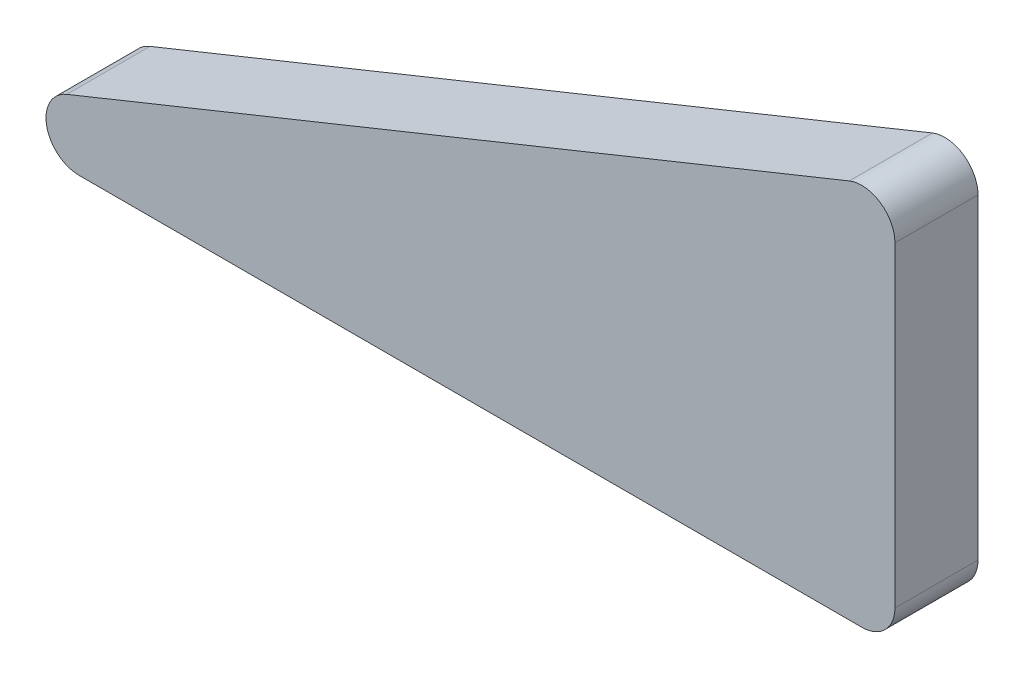
SolidWorks part; units mm, degrees
ref_plane "Front" through (0, 0, 0) normal (0, 0, 1) x (1, 0, 0)
ref_plane "Top" through (0, 0, 0) normal (0, 1, 0) x (1, 0, 0)
ref_plane "Right" through (0, 0, 0) normal (1, 0, 0) x (0, 0, -1)
sketch "Sketch1" plane through (0, 0, 0) normal (0, 0, 1) x (1, 0, 0)
  line L0 (0, 0) -> (29.6917, 0) construction
  line L1 (29.6917, 0) -> (29.6917, 12) construction
  line L2 (29.6917, 12) -> (0, 0) construction
  line L3 (5.143, 0) -> (28.6917, 0)
  line L4 (29.6917, 1) -> (29.6917, 10.5173)
  line L5 (28.3169, 11.4444) -> (4.7683, 1.9271)
  arc A0 (5.143, 0) -> (4.7683, 1.9271) centre (5.143, 1) cw
  arc A1 (28.6917, 0) -> (29.6917, 1) centre (28.6917, 1) ccw
  arc A2 (29.6917, 10.5173) -> (28.3169, 11.4444) centre (28.6917, 10.5173) ccw
  dimension "D3" = 1
  dimension "D1" = 29.6917
  dimension "D2" = 12
extrude "Boss-Extrude1" add sketch "Sketch1" along normal blind 2.5 contours L5 A0 L3 A1 L4 A2
